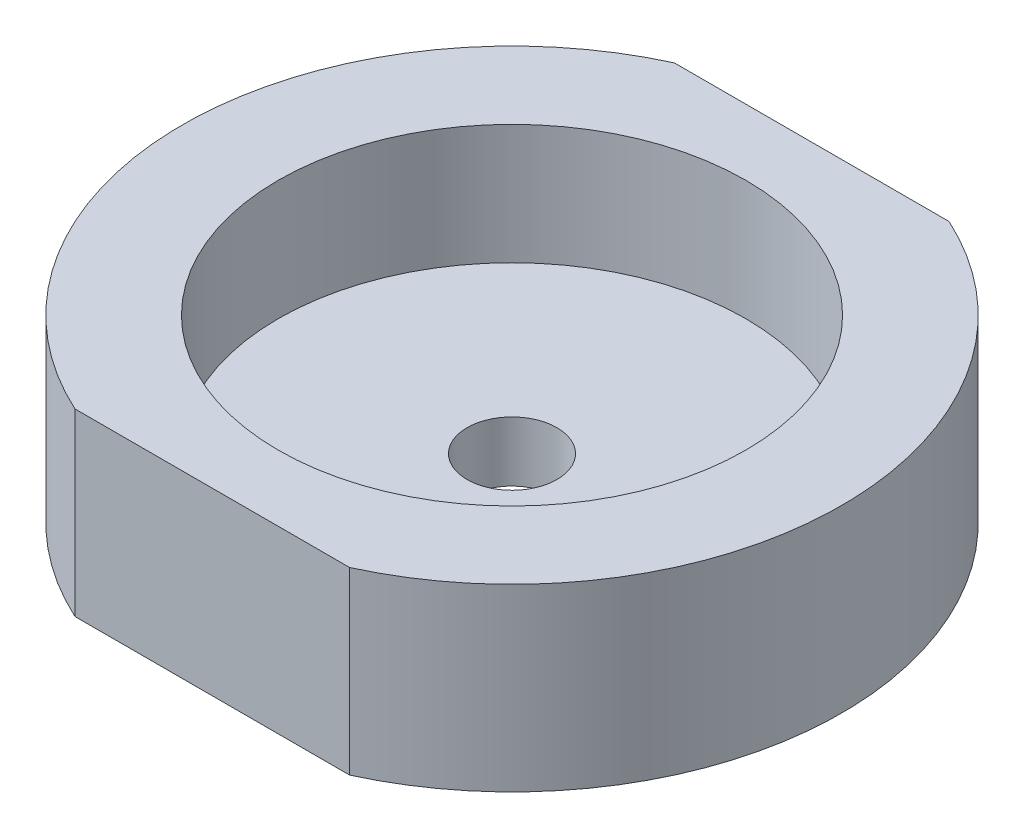
SolidWorks part; units mm, degrees
ref_plane "前视基准面" through (0, 0, 0) normal (0, 0, 1) x (1, 0, 0)
ref_plane "上视基准面" through (0, 0, 0) normal (0, 1, 0) x (1, 0, 0)
ref_plane "右视基准面" through (0, 0, 0) normal (1, 0, 0) x (0, 0, -1)
other "Configuration Table"
sketch "草图1" plane through (0, 0, 0) normal (0, 1, 0) x (1, 0, 0)
  line L1 (-6.1571, -5) -> (6.1571, -5)
  line L2 (-6.1571, -5) -> (-6.1571, 5)
  line L3 (-6.1571, 5) -> (6.1571, 5)
  line L4 (6.1571, -5) -> (6.1571, 5)
  line L5 (-6.1571, -5) -> (6.1571, 5) construction
  line L6 (-6.1571, 5) -> (6.1571, -5) construction
  circle A0 centre (0, 0) radius 5
  circle A1 centre (0, 0) radius 5.5
  dimension "D1" = 10
  dimension "D2" = 11
extrude "凸台-拉伸1" add sketch "草图1" along normal blind 3 contours L3 A1 L1 A0 | A0 | L1 A1 L3 A0
sketch "草图2" plane through (0, 3, 0) normal (0, 1, 0) x (1, 0, 0)
  circle A0 centre (0, 0) radius 3.9
  dimension "D1" = 7.8
extrude "切除-拉伸1" cut sketch "草图2" against normal blind 2
sketch "草图3" plane through (0, 1, 0) normal (0, -1, 0) x (-1, 0, 0)
  circle A0 centre (0, 0) radius 0.75
  dimension "D1" = 1.5
extrude "切除-拉伸2" cut sketch "草图3" along normal through all
